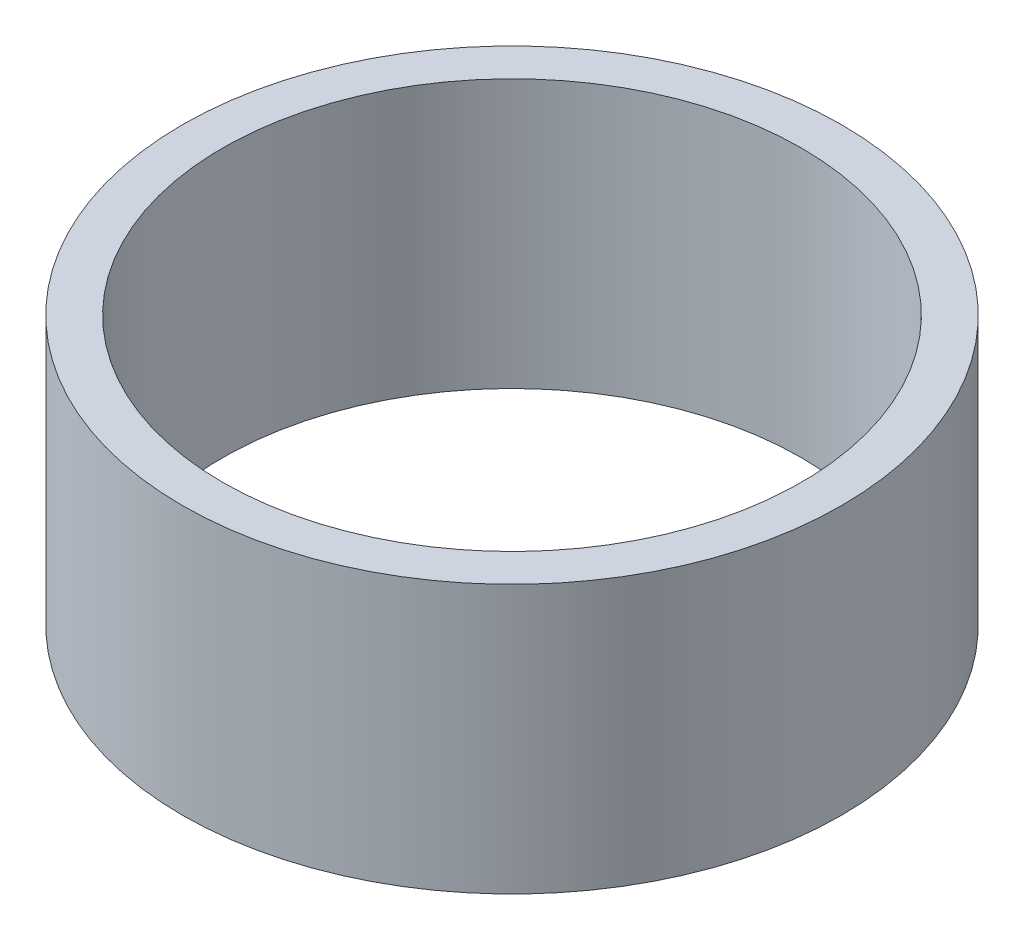
SolidWorks part; units mm, degrees
ref_plane "Front Plane" through (0, 0, 0) normal (0, 0, 1) x (1, 0, 0)
ref_plane "Top Plane" through (0, 0, 0) normal (0, 1, 0) x (1, 0, 0)
ref_plane "Right Plane" through (0, 0, 0) normal (1, 0, 0) x (0, 0, -1)
sketch "Sketch1" plane through (0, 0, 0) normal (0, 1, 0) x (1, 0, 0)
  line L0 (-60, 70) -> (60, 70)
  line L1 (-60, 70) -> (-60, -50)
  line L2 (-60, -50) -> (60, -50)
  line L3 (60, 70) -> (60, -50)
  line L4 (-45, -50) -> (45, -50)
  line L5 (45, -50) -> (45, 50)
  line L6 (45, 50) -> (-45, 50)
  line L7 (-45, 50) -> (-45, -50)
  line L8 (-45, 0) -> (45, 0) construction
  line L9 (-13, 13) -> (13, 13)
  line L10 (-13, 13) -> (-13, -13)
  line L11 (-13, -13) -> (13, -13)
  line L12 (13, 13) -> (13, -13)
  line L13 (0, 13) -> (0, -13) construction
  line L14 (13, 0) -> (-13, 0) construction
  circle A0 centre (0, 0) radius 18.3848 construction
  circle A1 centre (0, 0) radius 21.3848
  circle A2 centre (0, 0) radius 21.5848
  circle A3 centre (0, 0) radius 24.5848
sketch "Sketch2" plane through (0, 0, 0) normal (0, 1, 0) x (1, 0, 0)
  circle A0 centre (0, 0) radius 21.5848 construction
  circle A1 centre (0, 0) radius 21.5848
  circle A2 centre (0, 0) radius 24.5848 construction
  circle A3 centre (0, 0) radius 24.5848
extrude "Boss-Extrude1" add sketch "Sketch2" along normal mid plane 20
